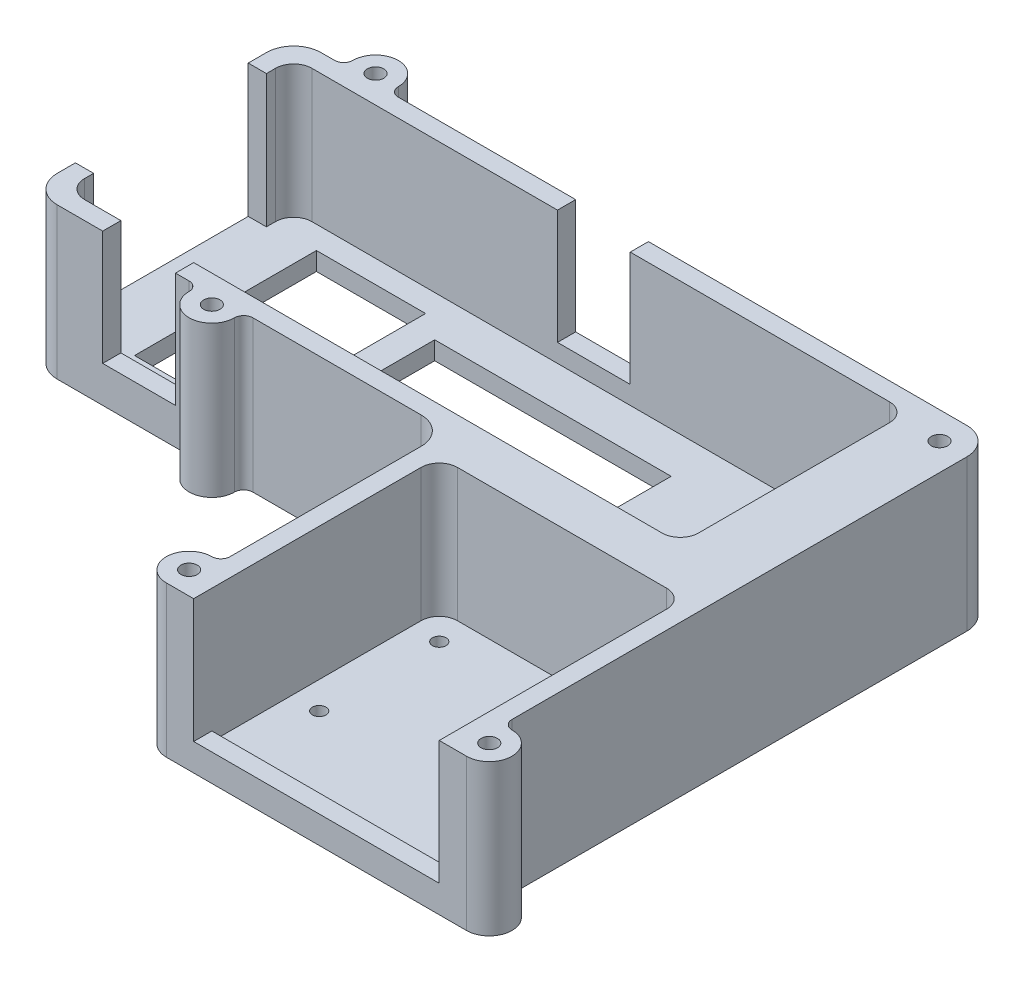
SolidWorks part; units mm, degrees
ref_plane "Alzado" through (0, 0, 0) normal (0, 0, 1) x (1, 0, 0)
ref_plane "Planta" through (0, 0, 0) normal (0, 1, 0) x (1, 0, 0)
ref_plane "Vista lateral" through (0, 0, 0) normal (1, 0, 0) x (0, 0, -1)
sketch "Croquis1" plane through (0, 0, 0) normal (0, 1, 0) x (1, 0, 0)
  line L5 (31, 29) -> (31, -30)
  line L6 (-46, 29) -> (31, 29)
  line L7 (-46, 0) -> (-46, 29)
  line L8 (0, 0) -> (-46, 0)
  line L9 (0, -30) -> (0, 0)
  line L10 (31, -30) -> (0, -30)
  line L12 (-39, 24.5) -> (-27, 24.5)
  line L13 (-39, 24.5) -> (-39, 4.5)
  line L14 (-39, 4.5) -> (-27, 4.5)
  line L15 (-27, 24.5) -> (-27, 4.5)
  line L16 (-24, 22.5) -> (2, 22.5)
  line L17 (-24, 22.5) -> (-24, 6.5)
  line L18 (-24, 6.5) -> (2, 6.5)
  line L19 (2, 22.5) -> (2, 6.5)
  point P1 (-46, 14.5)
  point P2 (-39, 14.5)
  point P17 (-24, 14.5)
  point P18 (-27, 14.5)
  dimension "D1" = 59
  dimension "D2" = 77
  dimension "D3" = 29
  dimension "D4" = 31
  dimension "D5" = 19
  dimension "D6" = 12
  dimension "D7" = 20
  dimension "D8" = 22
  dimension "D9" = 26
  dimension "D10" = 16
extrude "Saliente-Extruir1" add sketch "Croquis1" along normal blind 2
sketch "Croquis2" plane through (0, 2, 0) normal (0, 1, 0) x (1, 0, 0)
  line L1 (0, -30) -> (31, -30)
  line L2 (31, -30) -> (31, 29)
  line L3 (31, -30) -> (31, 29) construction
  line L4 (31, 29) -> (-46, 29)
  line L5 (31, 29) -> (-46, 29) construction
  line L7 (-46, 0) -> (0, 0)
  line L10 (29, -28) -> (29, -3)
  line L15 (23.5, 2) -> (23.5, 27)
  line L16 (29, 27) -> (-44, 27) construction
  line L17 (29, -28) -> (29, 27) construction
  line L18 (-44, 27) -> (-44, 2) construction
  line L19 (-44, 2) -> (2, 2) construction
  line L20 (23.5, 27) -> (-44, 27)
  line L22 (-46, 5) -> (-46, 0)
  line L23 (-46, 29) -> (-46, 0) construction
  line L24 (2, 2) -> (2, -28) construction
  line L25 (0, 0) -> (0, -30) construction
  line L26 (2, -28) -> (29, -28) construction
  line L27 (29, -28) -> (2, -28)
  line L28 (0, 0) -> (0, -30) construction
  line L31 (-44, 2) -> (23.5, 2)
  line L33 (2, -3) -> (29, -3)
  line L34 (-46, 29) -> (-46, 24)
  line L35 (-46, 29) -> (-46, 0) construction
  line L36 (-46, 24) -> (-44, 24)
  line L37 (-44, 24) -> (-44, 27)
  line L39 (-46, 5) -> (-44, 5)
  line L40 (-44, 5) -> (-44, 2)
  line L43 (0, 0) -> (0, -30)
  line L45 (2, -3) -> (2, -28)
  point P20 (-23, 0)
  dimension "D1" = 2
  dimension "D2" = 7.5
  dimension "D3" = 2
  dimension "D4" = 2
  dimension "D5" = 5
  dimension "D6" = 2
  dimension "D7" = 3
  dimension "D8" = 25
  dimension "D9" = 25
  dimension "D10" = 67.5
  dimension "D11" = 2
extrude "Saliente-Extruir2" add sketch "Croquis2" along normal blind 14.6
sketch "Croquis3" plane through (0, 0, 30) normal (0, 0, 1) x (1, 0, 0)
  line L1 (2, 3) -> (29, 3)
  line L2 (2, 3) -> (2, 16.6)
  line L3 (2, 16.6) -> (29, 16.6)
  line L4 (29, 3) -> (29, 16.6)
  line L5 (29, 16.6) -> (29, 2) construction
  line L6 (29, 2) -> (2, 2) construction
  line L7 (0, 16.6) -> (31, 16.6) construction
  line L9 (2, 16.6) -> (2, 2) construction
  dimension "D1" = 1
extrude "Cortar-Extruir1" cut sketch "Croquis3" against normal up to surface (2 mm away) up to face at (15.5, 9.3, 28)
fillet "Redondeo1" radius 3 4 edges at (31, 8.3, -29) (0, 8.3, 0) (-46, 8.3, 0) (-46, 8.3, -29)
fillet "Redondeo2" radius 2 6 edges at (23.5, 9.3, -2) (23.5, 9.3, -27) (29, 9.3, 3) (-44, 9.3, -2) (-44, 9.3, -27) (2, 9.3, 3)
sketch "Croquis4" plane through (0, 0, 0) normal (0, 0, 1) x (1, 0, 0)
  line L0 (-43, 16.6) -> (-3, 16.6) construction
  line L1 (-38, 16.6) -> (-30, 16.6)
  line L2 (-38, 16.6) -> (-38, 4)
  line L3 (-38, 4) -> (-30, 4)
  line L4 (-30, 16.6) -> (-30, 4)
  line L5 (21.5, 2) -> (-42, 2) construction
  line L6 (-46, 0) -> (-46, 16.6) construction
  dimension "D1" = 2
  dimension "D2" = 16
  dimension "D3" = 8
extrude "Cortar-Extruir2" cut sketch "Croquis4" against normal up to surface (2 mm away) up to face at (-10.25, 9.3, -2)
sketch "Croquis5" plane through (0, 0, -29) normal (0, 0, -1) x (-1, 0, 0)
  line L0 (-28, 16.6) -> (43, 16.6) construction
  line L1 (7, 16.6) -> (15, 16.6)
  line L2 (7, 16.6) -> (7, 4)
  line L3 (7, 4) -> (15, 4)
  line L4 (15, 16.6) -> (15, 4)
  line L5 (46, 16.6) -> (46, 0) construction
  line L7 (42, 2) -> (-21.5, 2) construction
  dimension "D1" = 8
  dimension "D2" = 39
  dimension "D3" = 2
extrude "Cortar-Extruir3" cut sketch "Croquis5" against normal up to surface (2 mm away) up to face at (-10.25, 9.3, -27)
sketch "Croquis6" plane through (0, 2, 0) normal (0, 1, 0) x (1, 0, 0)
  line L0 (4, -3) -> (27, -3) construction
  line L1 (5, -6) -> (26, -6) construction
  line L2 (5, -6) -> (5, -19.2) construction
  line L3 (5, -19.2) -> (26, -19.2) construction
  line L4 (26, -6) -> (26, -19.2) construction
  line L5 (29, -5) -> (29, -28) construction
  circle A1 centre (26, -6) radius 0.75
  circle A2 centre (5, -6) radius 0.75
  circle A3 centre (5, -19.2) radius 0.75
  circle A4 centre (26, -19.2) radius 0.75
  dimension "D1" = 1.5
  dimension "D2" = 3
  dimension "D3" = 24
  dimension "D4" = 21
  dimension "D5" = 13.2
extrude "Cortar-Extruir4" cut sketch "Croquis6" against normal up to surface (2 mm away) up to face at (-9.1, 0, -5.1243)
sketch "Croquis7" plane through (0, 16.6, 0) normal (0, 1, 0) x (1, 0, 0)
  line L0 (31, -30) -> (31, 26) construction
  line L1 (-15, 29) -> (-43, 29) construction
  line L3 (29, -30) -> (29, -5) construction
  line L5 (31, -30) -> (31, -24)
  line L10 (-1, -30) -> (0, -30)
  line L11 (15.5, -30) -> (15.5, -28) construction
  line L12 (2, -30) -> (29, -30) construction
  line L16 (2, -28) -> (29, -28) construction
  line L17 (-30, 2) -> (-30, 0) construction
  line L21 (-34.5, 29) -> (-41.5, 29)
  line L24 (-46, 26) -> (-46, 24) construction
  line L25 (-42, 27) -> (21.5, 27) construction
  line L26 (32, -30) -> (31, -30)
  line L27 (29, -30) -> (31, -30) construction
  line L31 (0, -30) -> (0, -24)
  line L32 (-21.5, 0) -> (-28.5, 0)
  line L33 (-30, 0) -> (-3, 0) construction
  line L34 (21.5, 2) -> (-42, 2) construction
  circle A2 centre (32, -27.5) radius 0.9
  arc A3 (32, -30) -> (32, -25) centre (32, -27.5) ccw
  arc A19 (-35.5, 30) -> (-40.5, 30) centre (-38, 30) ccw
  circle A21 centre (-38, 30) radius 0.9
  arc A26 (32, -25) -> (31, -24) centre (32, -24) cw
  arc A27 (-1, -25) -> (0, -24) centre (-1, -24) ccw
  arc A28 (-1, -30) -> (-1, -25) centre (-1, -27.5) cw
  circle A29 centre (-1, -27.5) radius 0.9
  arc A30 (-40.5, 30) -> (-41.5, 29) centre (-41.5, 30) cw
  arc A31 (-35.5, 30) -> (-34.5, 29) centre (-34.5, 30) ccw
  arc A36 (-27.5, -1) -> (-28.5, 0) centre (-28.5, -1) ccw
  arc A37 (-22.5, -1) -> (-21.5, 0) centre (-21.5, -1) cw
  circle A38 centre (-25, -1) radius 0.9
  arc A39 (-22.5, -1) -> (-27.5, -1) centre (-25, -1) cw
  dimension "D1" = 2.5
  dimension "D2" = 8
  dimension "D3" = 1.8
  dimension "D4" = 5
  dimension "D5" = 3
  dimension "D6" = 1.8
  dimension "D7" = 2.5
  dimension "D9" = 3
  dimension "D8" = 1.8
  dimension "D10" = 5
  dimension "D11" = 3
extrude "Saliente-Extruir3" add sketch "Croquis7" against normal up to surface (16.6 mm away) up to face at (26, 0, 18.45)
sketch "Croquis8" plane through (0, 16.6, 0) normal (0, 1, 0) x (1, 0, 0)
  line L0 (31, -24) -> (31, 26) construction
  line L1 (28, 29) -> (-7, 29) construction
  circle A0 centre (28, 26) radius 0.9
  dimension "D1" = 1.8
  dimension "D2" = 3
  dimension "D3" = 3
extrude "Cortar-Extruir5" cut sketch "Croquis8" against normal blind 6
